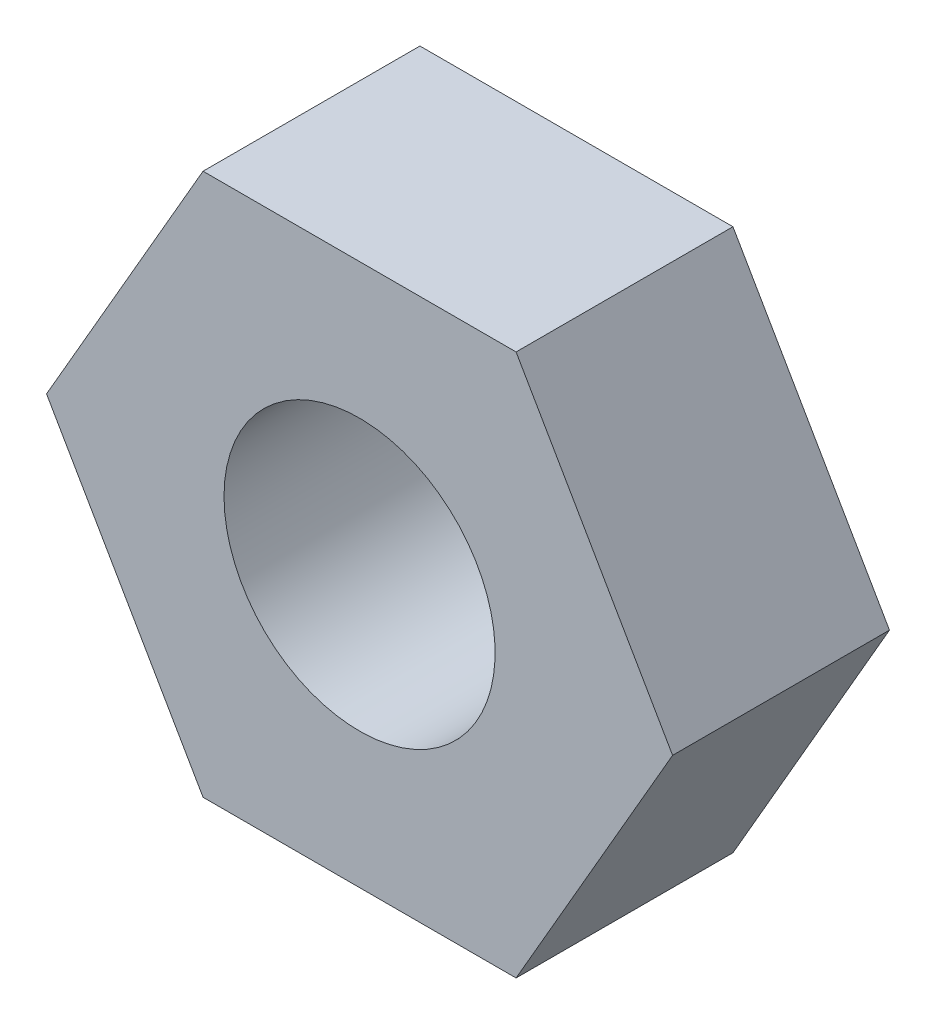
SolidWorks part; units mm, degrees
ref_plane "Front Plane" through (0, 0, 0) normal (0, 0, 1) x (1, 0, 0)
ref_plane "Top Plane" through (0, 0, 0) normal (0, 1, 0) x (1, 0, 0)
ref_plane "Right Plane" through (0, 0, 0) normal (1, 0, 0) x (0, 0, -1)
sketch "Sketch1" plane through (0, 0, 0) normal (0, 0, 1) x (1, 0, 0)
  line L1 (2.3094, 0) -> (1.1547, 2)
  line L2 (1.1547, 2) -> (-1.1547, 2)
  line L3 (-1.1547, 2) -> (-2.3094, 0)
  line L4 (-2.3094, 0) -> (-1.1547, -2)
  line L5 (-1.1547, -2) -> (1.1547, -2)
  line L6 (1.1547, -2) -> (2.3094, 0)
  circle A0 centre (0, 0) radius 2 construction
  dimension "D1" = 4
extrude "Boss-Extrude1" add sketch "Sketch1" along normal blind 1.6
sketch "Sketch2" plane through (0, 0, 0) normal (0, 0, -1) x (-1, 0, 0)
  circle A0 centre (0, 0) radius 1
  dimension "D1" = 2
extrude "Cut-Extrude1" cut sketch "Sketch2" against normal blind 1.6
